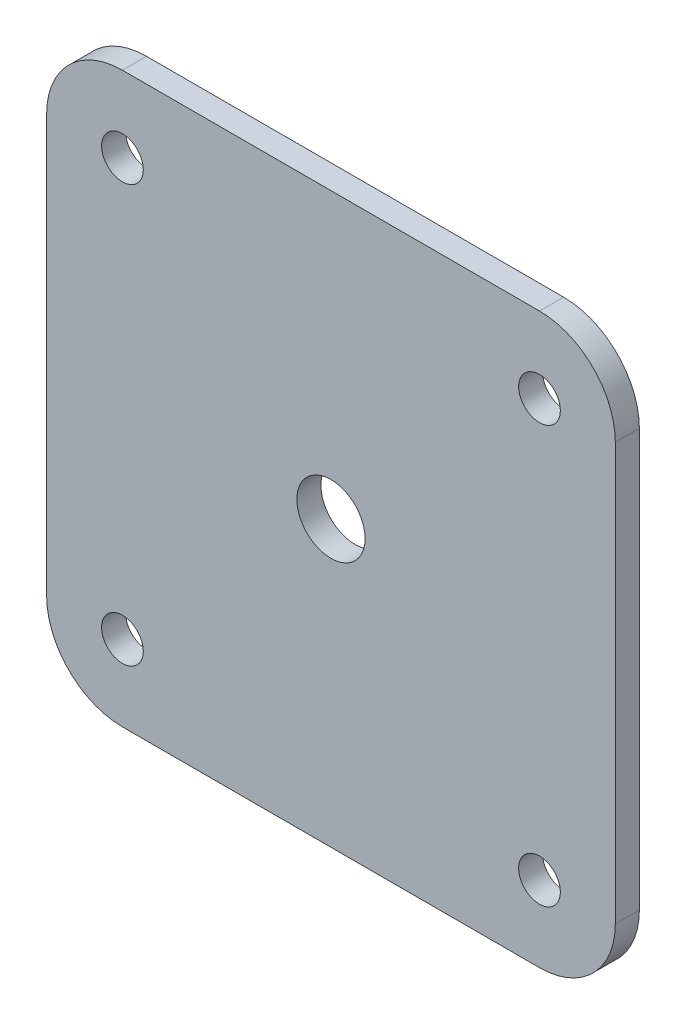
SolidWorks part; units mm, degrees
ref_plane "Front Plane" through (0, 0, 0) normal (0, 0, 1) x (1, 0, 0)
ref_plane "Top Plane" through (0, 0, 0) normal (0, 1, 0) x (1, 0, 0)
ref_plane "Right Plane" through (0, 0, 0) normal (1, 0, 0) x (0, 0, -1)
sketch "Sketch1" plane through (0, 0, 107.95) normal (0, 0, 1) x (1, 0, 0)
  line L1 (-37.5, 241.9) -> (37.5, 241.9)
  line L2 (-37.5, 241.9) -> (-37.5, 316.9)
  line L3 (-37.5, 316.9) -> (37.5, 316.9)
  line L4 (37.5, 241.9) -> (37.5, 316.9)
  line L5 (-37.5, 241.9) -> (37.5, 316.9) construction
  line L6 (-37.5, 316.9) -> (37.5, 241.9) construction
  circle A0 centre (0, 279.4) radius 3.25 construction
  circle A1 centre (0, 279.4) radius 3.25 construction
  dimension "D1" = 75
extrude "Boss-Extrude1" add sketch "Sketch1" along normal blind 3.175
sketch "Sketch2" plane through (0, 0, 111.125) normal (0, 0, 1) x (1, 0, 0)
  line L5 (27.5, 306.9) -> (-27.5, 306.9) construction
  line L7 (27.5, 306.9) -> (27.5, 251.9) construction
  line L8 (27.5, 251.9) -> (-27.5, 251.9) construction
  line L9 (-27.5, 306.9) -> (-27.5, 251.9) construction
  line L10 (27.5, 306.9) -> (-27.5, 251.9) construction
  line L11 (27.5, 251.9) -> (-27.5, 306.9) construction
  circle A7 centre (0, 279.4) radius 3.25 construction
  circle A8 centre (0, 279.4) radius 3.25 construction
  point P0 (0, 279.4)
  dimension "D1" = 55
sketch "Sketch5" plane through (0, 0, 111.125) normal (0, 0, 1) x (1, 0, 0)
  point P0 (0, 279.4)
hole_wizard "M8 Clearance Hole1" positions "Sketch5" profile "Sketch4" hole size "M8" standard "ANSI Metric" end condition through all
sketch "Sketch4" plane through (0, 279.4, 111.125) normal (1, 0, 0) x (0, -1, 0)
  line L0 (0, 0) -> (0, 3.175)
  line L1 (0, 3.175) -> (4.5, 3.175)
  line L2 (4.5, 3.175) -> (4.5, 0)
  line L5 (4.5, 0) -> (0, 0)
  line L11 (0, -6.35) -> (0, 107.95) construction
  dimension "Thru Hole Dia." = 9
  dimension "Thru Hole Depth" = 3.175
sketch "Sketch8" plane through (0, 0, 111.125) normal (0, 0, 1) x (1, 0, 0)
  point P0 (-27.5, 306.9)
  point P3 (27.5, 306.9)
  point P6 (27.5, 251.9)
  point P9 (-27.5, 251.9)
hole_wizard "M5 Clearance Hole1" positions "Sketch8" profile "Sketch7" hole size "M5" standard "ANSI Metric" end condition through all
sketch "Sketch7" plane through (-27.5, 306.9, 111.125) normal (1, 0, 0) x (0, -1, 0)
  line L0 (0, 0) -> (0, 3.175)
  line L1 (0, 3.175) -> (2.75, 3.175)
  line L2 (2.75, 3.175) -> (2.75, 0)
  line L5 (2.75, 0) -> (0, 0)
  line L11 (0, -6.35) -> (0, 107.95) construction
  dimension "Thru Hole Dia." = 5.5
  dimension "Thru Hole Depth" = 3.175
fillet "Fillet1" radius 10 4 edges at (37.5, 241.9, 109.5375) (-37.5, 241.9, 109.5375) (-37.5, 316.9, 109.5375) (37.5, 316.9, 109.5375)
